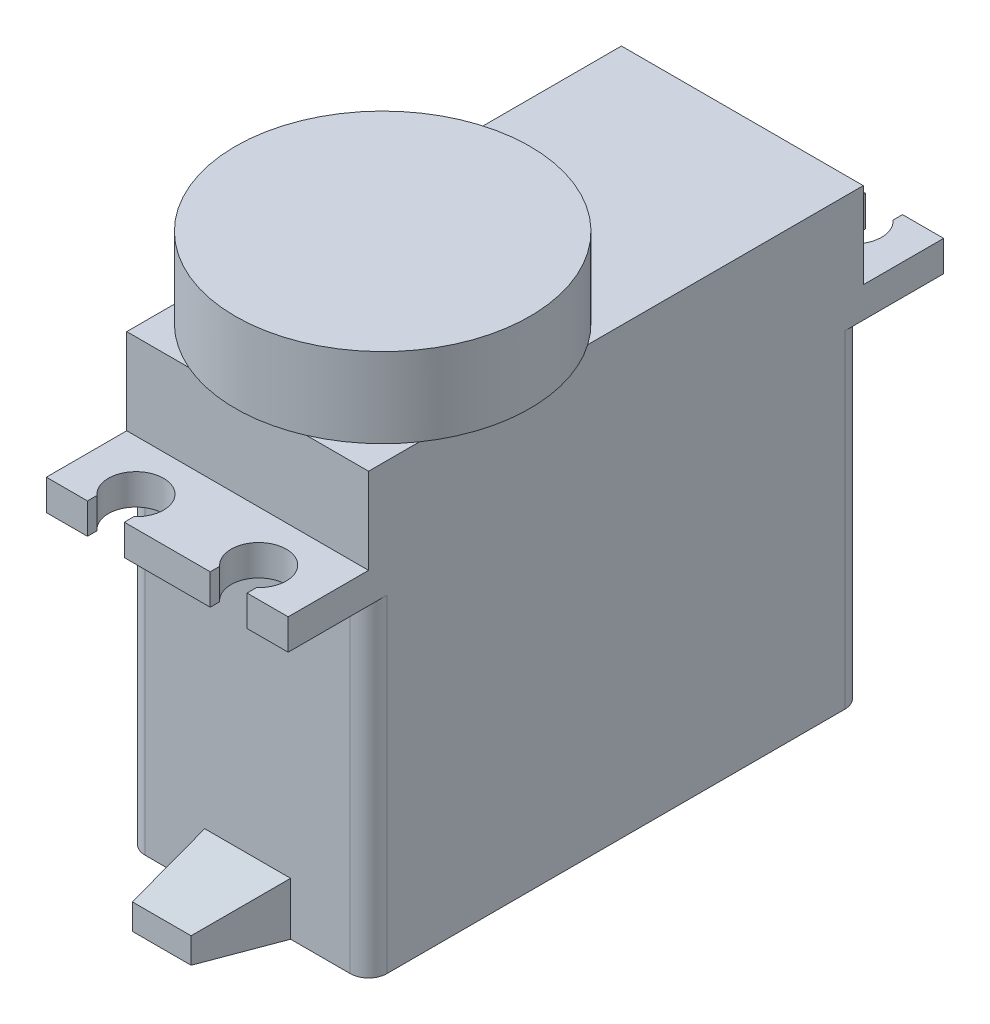
SolidWorks part; units mm, degrees
ref_plane "Plan de face" through (0, 0, 0) normal (0, 0, 1) x (1, 0, 0)
ref_plane "Plan de dessus" through (0, 0, 0) normal (0, 1, 0) x (1, 0, 0)
ref_plane "Plan de droite" through (0, 0, 0) normal (1, 0, 0) x (0, 0, -1)
sketch "Esquisse1" plane through (0, 0, 0) normal (1, 0, 0) x (0, 0, -1)
  line L1 (-20.15, -18.0975) -> (20.15, -18.0975)
  line L2 (-20.15, -18.0975) -> (-20.15, 18.0975)
  line L3 (-20.15, 18.0975) -> (20.15, 18.0975)
  line L4 (20.15, -18.0975) -> (20.15, 18.0975)
  line L5 (-20.15, -18.0975) -> (20.15, 18.0975) construction
  line L6 (-20.15, 18.0975) -> (20.15, -18.0975) construction
  point P0 (0, 0)
  dimension "D1" = 36.195
  dimension "D2" = 40.3
extrude "Boss.-Extru.1" add sketch "Esquisse1" along normal mid plane 19.7
sketch "Esquisse2" plane through (-9.85, 0, 0) normal (1, 0, 0) x (0, 0, -1)
  line L0 (-20.15, -18.0975) -> (20.15, -18.0975) construction
  line L1 (-26.7, 11.1025) -> (26.7, 11.1025)
  line L2 (-26.7, 11.1025) -> (-26.7, 8.6025)
  line L3 (-26.7, 8.6025) -> (26.7, 8.6025)
  line L4 (26.7, 11.1025) -> (26.7, 8.6025)
  line L5 (0, 10.835) -> (0, -10.835) construction
  point P6 (0, 11.1025)
  dimension "D1" = 2.5
  dimension "D2" = 53.4
  dimension "D3" = 26.7
extrude "Boss.-Extru.2" add sketch "Esquisse2" along normal up to surface (19.7 mm away) up to face at (9.85, 0, 0)
sketch "Esquisse3" plane through (0, 18.0975, 0) normal (0, 1, 0) x (1, 0, 0)
  line L0 (9.85, -20.15) -> (-9.85, -20.15) construction
  circle A0 centre (0, -9.15) radius 12
  point P4 (0, -20.15)
  dimension "D1" = 24
  dimension "D2" = 11
extrude "Boss.-Extru.3" add sketch "Esquisse3" along normal blind 6.5
sketch "Esquisse5" plane through (0, 0, 20.15) normal (0, 0, 1) x (1, 0, 0)
  line L0 (9.85, -18.0975) -> (-9.85, -18.0975) construction
  line L1 (3.5, -13.7975) -> (-3.5, -13.7975)
  line L2 (3.5, -13.7975) -> (3.5, -18.0975)
  line L3 (3.5, -18.0975) -> (-3.5, -18.0975)
  line L4 (-3.5, -13.7975) -> (-3.5, -18.0975)
  line L5 (0, -19.9072) -> (0, 19.9072) construction
  point P6 (0, -18.0975)
  dimension "D1" = 7
  dimension "D2" = 4.3
extrude "Boss.-Extru.4" add sketch "Esquisse5" along normal blind 7 draft 9
sketch "Esquisse6" plane through (0, 11.1025, 0) normal (0, 1, 0) x (1, 0, 0)
  line L0 (0, -23.4823) -> (0, 23.4822) construction
  line L1 (-5, 24.25) -> (5, 24.25) construction
  line L2 (-5, 24.25) -> (-5, -24.25) construction
  line L3 (-5, -24.25) -> (5, -24.25) construction
  line L4 (5, 24.25) -> (5, -24.25) construction
  line L5 (-13.2, 0) -> (13.2, 0) construction
  point P4 (0, -24.25)
  point P7 (-5, 0)
  dimension "D1" = 10
  dimension "D2" = 48.5
hole_wizard "Diamètre du perçage Ø4.5 (4.5)1" positions "Esquisse7" profile "Esquisse8" hole size "Ø4.5" standard "Ansi Metric"
sketch "Esquisse7" plane through (0, 11.1025, 0) normal (0, 1, 0) x (1, 0, 0)
  point P0 (5, 24.25)
  point P3 (-5, 24.25)
  point P6 (5, -24.25)
  point P9 (-5, -24.25)
sketch "Esquisse8" plane through (5, 11.1025, -24.25) normal (1, 0, 0) x (0, 0, 1)
  line L0 (0, 0) -> (0, 4.5519)
  line L1 (0, 4.5519) -> (2.25, 3.2)
  line L2 (2.25, 3.2) -> (2.25, 0)
  line L5 (2.25, 0) -> (0, 0)
  line L10 (0, 4.5519) -> (-2.25, 3.2) construction
  line L11 (0, -6.35) -> (0, 107.95) construction
  dimension "Diamètre du perçage" = 4.5
  dimension "Profondeur du perçage" = 3.2
  dimension "Angle de pointe" = 118
sketch "Esquisse9" plane through (0, 11.1025, 0) normal (0, 1, 0) x (1, 0, 0)
  line L0 (9.85, 26.7) -> (-9.85, 26.7) construction
  line L1 (-6.5, 26.7) -> (-3.5, 26.7)
  line L2 (-6.5, 26.7) -> (-6.5, 25.9271)
  line L3 (-6.5, 25.9271) -> (-3.5, 25.9271)
  line L4 (-3.5, 26.7) -> (-3.5, 25.9271)
  circle A0 centre (-5, 24.25) radius 2.25 construction
  dimension "D1" = 3
extrude "Enlèv. mat.-Extru.1" cut sketch "Esquisse9" against normal through all
mirror "Symétrie1" about plane through (0, 0, 0) normal (1, 0, 0) of "Enlèv. mat.-Extru.1"
mirror "Symétrie2" about plane through (0, 0, 0) normal (0, 0, 1) of "Symétrie1", "Enlèv. mat.-Extru.1"
fillet "Congé1" radius 1.5 4 edges at (9.85, -4.7475, 20.15) (-9.85, -4.7475, 20.15) (9.85, -4.7475, -20.15) (-9.85, -4.7475, -20.15)
